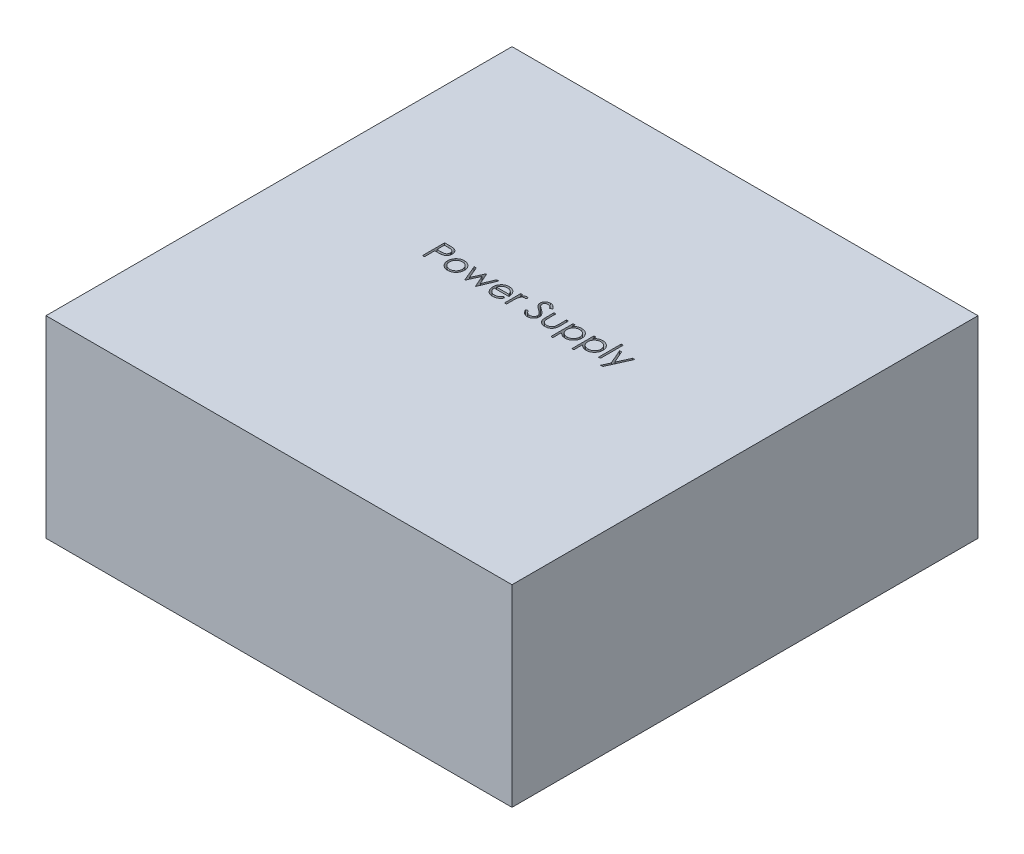
SolidWorks part; units mm, degrees
ref_plane "Front Plane" through (0, 0, 0) normal (0, 0, 1) x (1, 0, 0)
ref_plane "Top Plane" through (0, 0, 0) normal (0, 1, 0) x (1, 0, 0)
ref_plane "Right Plane" through (0, 0, 0) normal (1, 0, 0) x (0, 0, -1)
sketch "Sketch1" plane through (0, 0, 0) normal (0, 1, 0) x (1, 0, 0)
  line L1 (-73.66, 73.66) -> (0, 73.66)
  line L2 (-73.66, 73.66) -> (-73.66, 0)
  line L3 (-73.66, 0) -> (0, 0)
  line L4 (0, 73.66) -> (0, 0)
  point P4 (0, 0)
  dimension "D1" = 73.66
  dimension "D2" = 73.66
extrude "Boss-Extrude1" add sketch "Sketch1" along normal blind 30.48 contours L2 L1 L4 L3
sketch "Sketch2" plane through (0, 30.48, 0) normal (0, 1, 0) x (1, 0, 0)
  line L0 (-73.66, 37.9892) -> (0, 37.9892) construction
  line L1 (0, 73.66) -> (0, 0) construction
  line L2 (-73.66, 73.66) -> (-73.66, 0) construction
  text T0 "Power Supply"
  point P4 (-73.66, 37.9892)
  point P7 (0, 37.9892)
extrude "Cut-Extrude1" cut sketch "Sketch2" against normal blind 3
